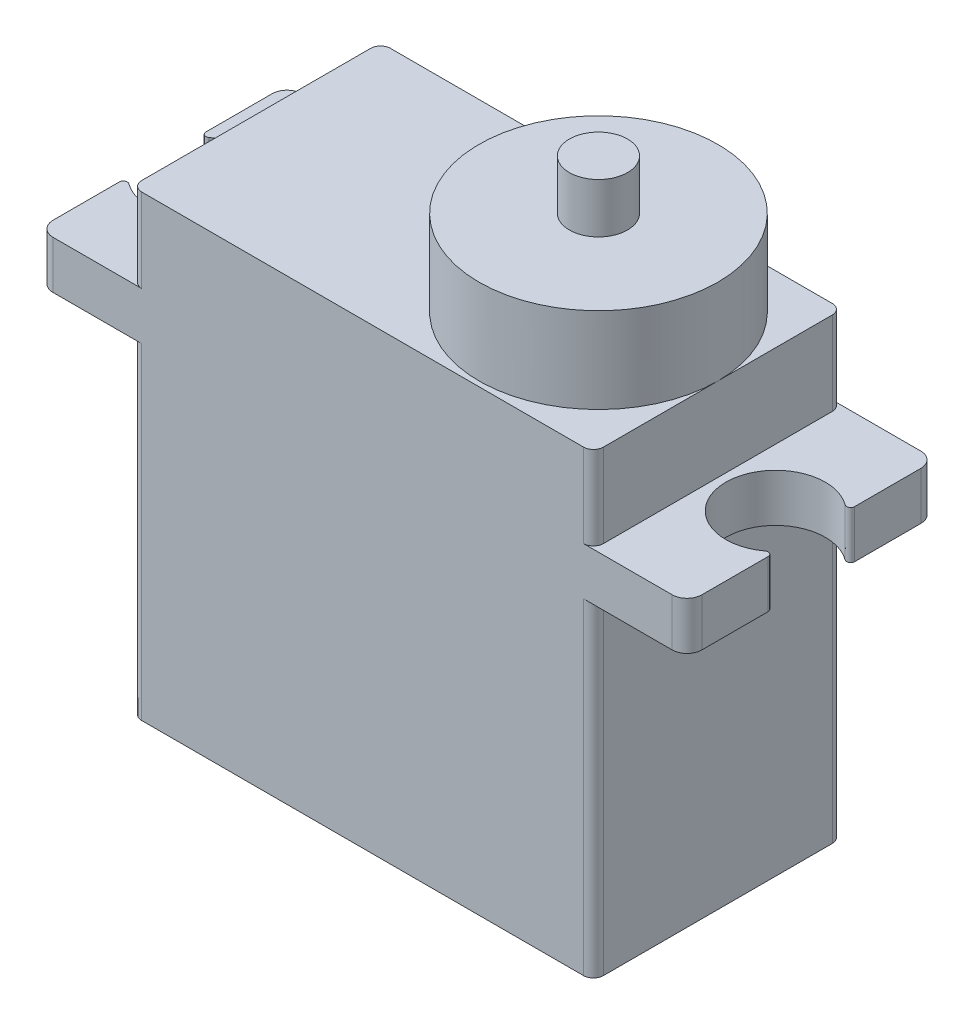
SolidWorks part; units mm, degrees
ref_plane "Plan de face" through (0, 0, 0) normal (0, 0, 1) x (1, 0, 0)
ref_plane "Plan de dessus" through (0, 0, 0) normal (0, 1, 0) x (1, 0, 0)
ref_plane "Plan de droite" through (0, 0, 0) normal (1, 0, 0) x (0, 0, -1)
sketch "Esquisse1" plane through (0, 0, 0) normal (0, 1, 0) x (1, 0, 0)
  line L1 (-11.6, -6.25) -> (11.6, -6.25)
  line L2 (-11.6, -6.25) -> (-11.6, 6.25)
  line L3 (-11.6, 6.25) -> (11.6, 6.25)
  line L4 (11.6, -6.25) -> (11.6, 6.25)
  line L5 (-11.6, -6.25) -> (11.6, 6.25) construction
  line L6 (-11.6, 6.25) -> (11.6, -6.25) construction
  point P0 (0, 0)
  dimension "D1" = 23.2
  dimension "D2" = 12.5
extrude "Boss.-Extru.1" add sketch "Esquisse1" along normal blind 23
sketch "Esquisse2" plane through (0, 0, 6.25) normal (0, 0, 1) x (1, 0, 0)
  line L0 (11.6, 0) -> (11.6, 16.4) construction
  line L1 (11.6, 23) -> (11.6, 0) construction
  line L2 (11.6, 16.4) -> (11.6, 18.8) construction
  line L3 (-11.6, 23) -> (-11.6, 0) construction
  line L4 (11.6, 16.4) -> (16.3, 16.4)
  line L5 (11.6, 16.4) -> (11.6, 18.8)
  line L6 (11.6, 18.8) -> (16.3, 18.8)
  line L7 (16.3, 16.4) -> (16.3, 18.8)
  line L8 (-11.6, 16.4) -> (-16.3, 16.4)
  line L9 (-11.6, 16.4) -> (-11.6, 18.8)
  line L10 (-11.6, 18.8) -> (-16.3, 18.8)
  line L11 (-16.3, 16.4) -> (-16.3, 18.8)
  line L12 (11.6, 18.8) -> (11.6, 23) construction
  dimension "D1" = 16.4
  dimension "D2" = 2.4
  dimension "D3" = 4.7
  dimension "D4" = 4.7
extrude "Boss.-Extru.2" add sketch "Esquisse2" against normal blind 12.5
fillet "Congé1" radius 0.75 4 edges at (16.3, 17.6, -6.25) (16.3, 17.6, 6.25) (-16.3, 17.6, -6.25) (-16.3, 17.6, 6.25)
sketch "Esquisse3" plane through (0, 23, 0) normal (0, 1, 0) x (1, 0, 0)
  line L0 (0, 0) -> (-14.5, 0) construction
  line L1 (0, 0) -> (14.5, 0) construction
  circle A0 centre (-14.5, 0) radius 2.5
  circle A1 centre (14.5, 0) radius 2.5
  dimension "D3" = 5
  dimension "D4" = 5
  dimension "D1" = 14.5
  dimension "D2" = 14.5
extrude "Enlèv. mat.-Extru.1" cut sketch "Esquisse3" against normal blind 11.8
fillet "Congé2" radius 0.2 4 edges at (16.3, 17.6, 1.7349) (16.3, 17.6, -1.7349) (-16.3, 17.6, 1.7349) (-16.3, 17.6, -1.7349)
fillet "Congé3" radius 0.5 8 edges at (-11.6, 8.2, -6.25) (-11.6, 20.9, -6.25) (11.6, 20.9, -6.25) (11.6, 8.2, -6.25) (11.6, 20.9, 6.25) (-11.6, 20.9, 6.25) (11.6, 8.2, 6.25) (-11.6, 8.2, 6.25)
sketch "Esquisse5" plane through (0, 23, 0) normal (0, 1, 0) x (1, 0, 0)
  line L0 (11.6, -5.75) -> (11.6, 5.75) construction
  circle A0 centre (5.6, 0) radius 1.205
  circle A1 centre (5.6, 0) radius 6
  dimension "D1" = 2.41
  dimension "D2" = 12
  dimension "D3" = 6
extrude "Boss.-Extru.3" add sketch "Esquisse5" along normal blind 4.3 contours A1
sketch "Esquisse6" plane through (0, 27.3, 0) normal (0, 1, 0) x (1, 0, 0)
  circle A0 centre (5.6, 0) radius 1.4612
extrude "Boss.-Extru.4" add sketch "Esquisse6" along normal blind 2.5
